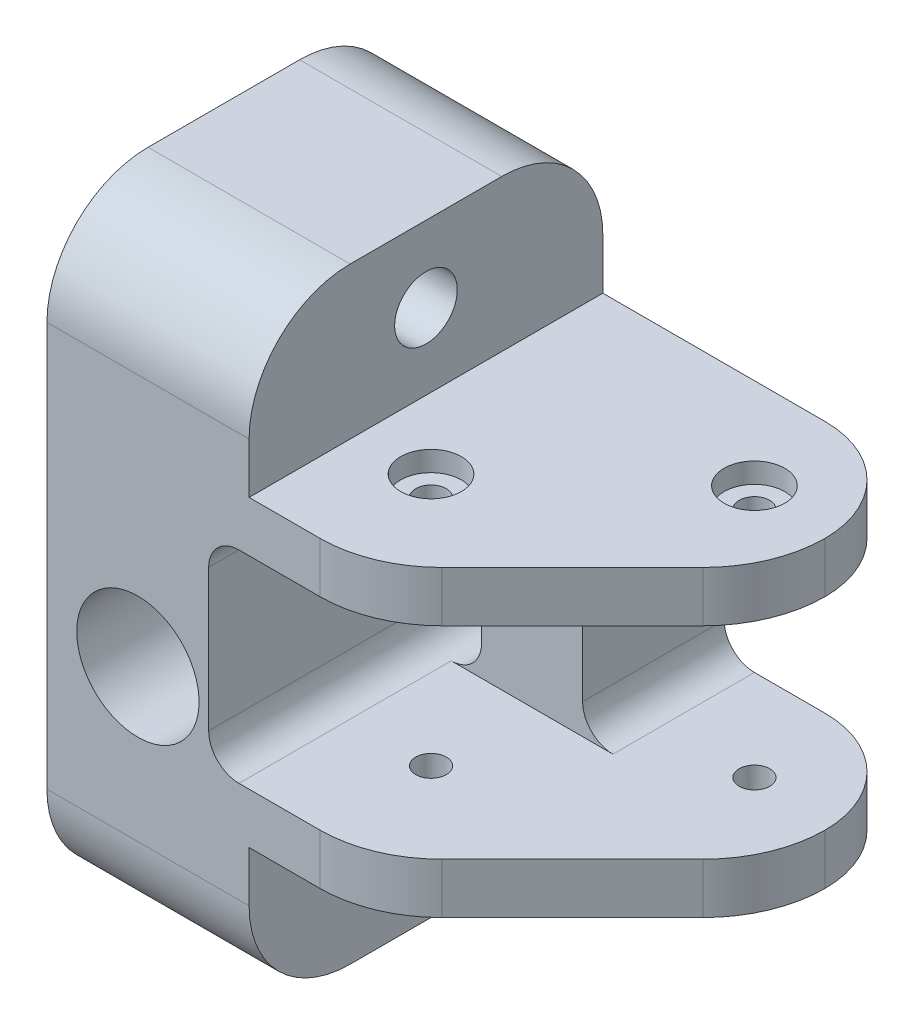
SolidWorks part; units mm, degrees
ref_plane "前视基准面" through (0, 0, 0) normal (0, 0, 1) x (1, 0, 0)
ref_plane "上视基准面" through (0, 0, 0) normal (0, 1, 0) x (1, 0, 0)
ref_plane "右视基准面" through (0, 0, 0) normal (1, 0, 0) x (0, 0, -1)
other "Configuration Table"
sketch "草图1" plane through (0, 0, 0) normal (0, 1, 0) x (1, 0, 0)
  line L0 (-25, -17.5) -> (5, -17.5)
  line L1 (25, 17.5) -> (25, 2.5)
  line L2 (25, 2.5) -> (5, -17.5)
  line L7 (-25, -17.5) -> (-25, 17.5)
  line L8 (-25, 17.5) -> (25, 17.5)
extrude "凸台-拉伸1" add sketch "草图1" along normal blind 60 contours L2 L0 L7 L8 L1
sketch "草图2" plane through (0, 0, -17.5) normal (0, 0, -1) x (-1, 0, 0)
  line L0 (25, 0) -> (7, 0)
  line L1 (25, 0) -> (-25, 0) construction
  line L2 (7, 0) -> (7, 60)
  line L3 (25, 60) -> (-25, 60) construction
  line L5 (-25, 60) -> (7, 60)
  line L6 (-25, 60) -> (-25, 45)
  line L7 (-25, 45) -> (7, 45)
  line L8 (7, 60) -> (7, 45)
  line L9 (-25, 0) -> (7, 0)
  line L10 (-25, 0) -> (-25, 15)
  line L11 (-25, 15) -> (7, 15)
  line L12 (7, 0) -> (7, 15)
  line M11 (-25, 0) -> (25, 0)
  line M13 (25, 60) -> (-25, 60)
  line M14 (-25, 60) -> (-25, 0)
extrude "切除-拉伸1" cut sketch "草图2" against normal blind 60 contours L7 L2 M14 M13 | L11 L2 M14 M11
sketch "草图3" plane through (-25, 0, 0) normal (-1, 0, 0) x (0, 0, 1)
  line L0 (-17.5, 60) -> (17.5, 0)
  line L1 (0, 30) -> (0, 52.5)
  line L2 (0, 30) -> (0, 7.5)
  circle A0 centre (0, 52.5) radius 3
  circle A1 centre (0, 7.5) radius 3
extrude "切除-拉伸2" cut sketch "草图3" against normal blind 30
sketch "草图4" plane through (-25, 0, 0) normal (-1, 0, 0) x (0, 0, 1)
  line L1 (-17.5, 60) -> (-7.5, 60)
  line L2 (-17.5, 60) -> (-17.5, 50)
  line L5 (17.5, 60) -> (7.5, 60)
  line L6 (17.5, 60) -> (17.5, 50)
  line L9 (-17.5, 0) -> (-7.5, 0)
  line L10 (-17.5, 0) -> (-17.5, 10)
  line L13 (17.5, 0) -> (7.5, 0)
  line L14 (17.5, 0) -> (17.5, 10)
  arc A0 (-17.5, 50) -> (-7.5, 60) centre (-7.5, 50) cw
  arc A1 (17.5, 50) -> (7.5, 60) centre (7.5, 50) ccw
  arc A2 (-17.5, 10) -> (-7.5, 0) centre (-7.5, 10) ccw
  arc A3 (17.5, 10) -> (7.5, 0) centre (7.5, 10) cw
  line M20 (-17.5, 0) -> (17.5, 0)
  line M21 (17.5, 0) -> (17.5, 60)
  line M22 (17.5, 60) -> (-17.5, 60)
  line M23 (-17.5, 60) -> (-17.5, 0)
extrude "切除-拉伸3" cut sketch "草图4" against normal blind 30 contours A0 M23 M22 | A1 M21 M22 | A3 M21 M20 | A2 M23 M20
sketch "草图5" plane through (0, 0, -17.5) normal (0, 0, -1) x (-1, 0, 0)
  line L0 (5, 37) -> (5, 23)
  line L2 (11, 37) -> (11, 23)
  arc A0 (11, 23) -> (5, 23) centre (8, 23) cw
  arc A1 (5, 37) -> (11, 37) centre (8, 37) cw
extrude "切除-拉伸4" cut sketch "草图5" against normal blind 50
sketch "草图6" plane through (0, 0, -17.5) normal (0, 0, -1) x (-1, 0, 0)
  circle A1 centre (18, 25) radius 5
extrude "切除-拉伸5" cut sketch "草图6" against normal blind 50
sketch "草图7" plane through (0, 0, -17.5) normal (0, 0, -1) x (-1, 0, 0)
  line L0 (-8, 40) -> (-25, 40)
  line L1 (-25, 45) -> (-25, 15) construction
  line L2 (-5, 23) -> (-5, 30)
  line L3 (5, 30) -> (-5, 30)
  line L4 (5, 37) -> (5, 23) construction
  line L5 (-5, 37) -> (-5, 30)
  line L6 (-8, 20) -> (-25, 20)
  line L7 (-25, 20) -> (-25, 40)
  arc A2 (-5, 37) -> (-8, 40) centre (-8, 37) ccw
  arc A3 (-8, 20) -> (-5, 23) centre (-8, 23) ccw
  line M26 (-25, 45) -> (-25, 15)
extrude "切除-拉伸6" cut sketch "草图7" against normal blind 50 contours L6 A3 L2 L5 A2 L0 M26
sketch "草图8" plane through (5, 0, 0) normal (1, 0, 0) x (0, 0, -1)
  line L0 (17.5, 37) -> (3.5, 37)
  line L1 (-17.5, 37) -> (17.5, 37) construction
  line L2 (3.5, 37) -> (3.5, 40)
  line L3 (-14.5, 40) -> (17.5, 40) construction
  line L5 (3.5, 40) -> (-17.5, 40)
  line L6 (3.5, 40) -> (3.5, 20)
  line L7 (3.5, 20) -> (-17.5, 20)
  line L8 (-17.5, 40) -> (-17.5, 20)
  line M6 (-17.5, 37) -> (-17.5, 23)
  line M7 (-17.5, 23) -> (17.5, 23)
  line M9 (17.5, 37) -> (-17.5, 37)
extrude "切除-拉伸7" cut sketch "草图8" against normal blind 13 contours L6 M9 M6 M7 | L5 L8 L2 M9 | L8 L7 L6 M7
sketch "草图9" plane through (5, 0, 0) normal (-1, 0, 0) x (0, 0, 1)
  line L1 (-3.5, 40) -> (17.5, 40)
  line L2 (-3.5, 40) -> (-3.5, 37)
  line L3 (-3.5, 37) -> (17.5, 37)
  line L4 (17.5, 40) -> (17.5, 37)
  line L5 (-3.5, 20) -> (17.5, 20)
  line L6 (-3.5, 20) -> (-3.5, 23)
  line L7 (-3.5, 23) -> (17.5, 23)
  line L8 (17.5, 20) -> (17.5, 23)
extrude "切除-拉伸8" cut sketch "草图9" against normal blind 13
sketch "草图10" plane through (0, 15, 0) normal (0, -1, 0) x (-1, 0, 0)
  line L0 (-25, 2.5) -> (-21.4645, -1.0355)
  line L1 (-5, -17.5) -> (-25, 2.5) construction
  line L2 (-25, 2.5) -> (-25, 7.5)
  line L3 (-25, 2.5) -> (-25, 17.5) construction
  line L9 (-25, 17.5) -> (-15, 17.5)
  line L10 (-25, 17.5) -> (-25, 7.5)
  arc A0 (-21.4645, -1.0355) -> (-25, 7.5) centre (-12.9289, 7.5) cw
  arc A2 (-15, 17.5) -> (-25, 7.5) centre (-15, 7.5) ccw
  line M10 (7, 17.5) -> (-25, 17.5)
  line M11 (-25, 17.5) -> (-25, 2.5)
extrude "切除-拉伸10" cut sketch "草图10" against normal blind 50 contours A2 M10 M11 | L2 L0 A0
sketch "草图11" plane through (0, 45, 0) normal (0, 1, 0) x (1, 0, 0)
  line L0 (5, -17.5) -> (8.5355, -13.9645)
  line L1 (5, -17.5) -> (21.4645, -1.0355) construction
  line L2 (5, -17.5) -> (0, -17.5)
  line L3 (5, -17.5) -> (-7, -17.5) construction
  arc A0 (0, -17.5) -> (8.5355, -13.9645) centre (0, -5.4289) ccw
extrude "切除-拉伸11" cut sketch "草图11" against normal blind 50 contours A0 L0 L2
sketch "草图15" plane through (0, 20, 0) normal (0, 1, 0) x (1, 0, 0)
  line L0 (8, 17.5) -> (8, 8.5)
  line L2 (8, 3.5) -> (8, 17.5) construction
  line L3 (8, 8.5) -> (17, 8.5)
  circle A0 centre (17, 8.5) radius 1.51
extrude "切除-拉伸14" cut sketch "草图15" against normal blind 100
sketch "草图16" plane through (0, 15, 0) normal (0, -1, 0) x (1, 0, 0)
  circle A0 centre (17, -8.5) radius 1.51
extrude "切除-拉伸15" cut sketch "草图16" against normal blind 100 contours A0
sketch "草图17" plane through (0, 40, 0) normal (0, -1, 0) x (-1, 0, 0)
  line L0 (-8, 3.5) -> (8, 3.5)
  line L2 (0, 3.5) -> (0, -6.5)
  circle A1 centre (0, -6.5) radius 1.51
extrude "切除-拉伸16" cut sketch "草图17" against normal blind 100
sketch "草图18" plane through (0, 45, 0) normal (0, 1, 0) x (1, 0, 0)
  circle A0 centre (0, -6.5) radius 1.51
extrude "切除-拉伸17" cut sketch "草图18" against normal blind 100
sketch "草图21" plane through (0, 45, 0) normal (0, 1, 0) x (1, 0, 0)
  circle A0 centre (0, -6.5) radius 3
  circle A1 centre (17, 8.5) radius 3
extrude "切除-拉伸18" cut sketch "草图21" against normal blind 2 contours A1 | A0
sketch "草图22" plane through (0, 15, 0) normal (0, -1, 0) x (-1, 0, 0)
  circle A0 centre (0, -6.5) radius 3
  circle A1 centre (-17, 8.5) radius 3
extrude "切除-拉伸19" cut sketch "草图22" against normal blind 2 contours A0 | A1
sketch "草图23" plane through (0, 0, -17.5) normal (0, 0, -1) x (-1, 0, 0)
  circle A0 centre (18, 25) radius 5.05
extrude "切除-拉伸20" cut sketch "草图23" against normal blind 100
sketch "草图24" plane through (-25, 0, 0) normal (-1, 0, 0) x (0, 0, 1)
  circle A0 centre (0, 52.5) radius 3.05
  circle A1 centre (0, 7.5) radius 3.05
extrude "切除-拉伸21" cut sketch "草图24" against normal blind 100 contours A0
sketch "草图25" plane through (-25, 0, 0) normal (-1, 0, 0) x (0, 0, 1)
  circle A1 centre (0, 7.5) radius 3.05
extrude "切除-拉伸22" cut sketch "草图25" against normal blind 30 contours A1
sketch "草图27" plane through (0, 0, -17.5) normal (0, 0, -1) x (-1, 0, 0)
  circle A0 centre (18, 25) radius 6.05
extrude "切除-拉伸23" cut sketch "草图27" against normal blind 50
sketch "草图29" plane through (-25, 0, 0) normal (-1, 0, 0) x (0, 0, 1)
  line L0 (-7.5, 60) -> (7.5, 60)
  line L3 (17.5, 50) -> (17.5, 10)
  line L6 (7.5, 0) -> (-7.5, 0)
  line L9 (-17.5, 10) -> (-17.5, 50)
  circle A0 centre (0, 52.5) radius 3.05
  circle A1 centre (0, 7.5) radius 3.05
  arc A2 (17.5, 50) -> (7.5, 60) centre (7.5, 50) ccw
  arc A3 (17.5, 50) -> (7.5, 60) centre (7.5, 50) ccw construction
  arc A4 (-17.5, 50) -> (-7.5, 60) centre (-7.5, 50) cw
  arc A5 (-17.5, 10) -> (-7.5, 0) centre (-7.5, 10) ccw
  arc A6 (17.5, 10) -> (7.5, 0) centre (7.5, 10) cw
  arc A7 (7.5, 0) -> (17.5, 10) centre (7.5, 10) ccw construction
extrude "凸台-拉伸2" add sketch "草图29" along normal blind 2 contours L3 A6 L6 A5 L9 A4 L0 A2
sketch "草图30" plane through (-27, 0, 0) normal (-1, 0, 0) x (0, 0, 1)
  circle A0 centre (0, 52.5) radius 3.1
  circle A1 centre (0, 7.5) radius 3.1
extrude "切除-拉伸24" cut sketch "草图30" against normal blind 30 contours A1 | A0
